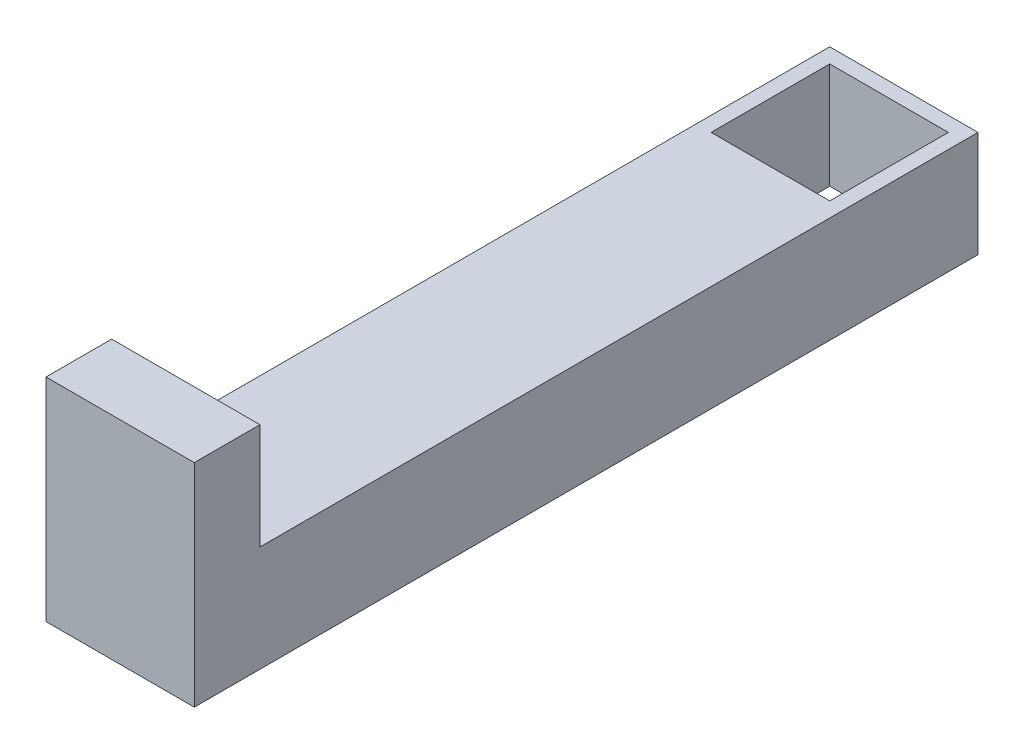
SolidWorks part; units mm, degrees
ref_plane "Front Plane" through (0, 0, 0) normal (0, 0, 1) x (1, 0, 0)
ref_plane "Top Plane" through (0, 0, 0) normal (0, 1, 0) x (1, 0, 0)
ref_plane "Right Plane" through (0, 0, 0) normal (1, 0, 0) x (0, 0, -1)
sketch "Sketch1" plane through (0, 0, 0) normal (0, 1, 0) x (1, 0, 0)
  line L1 (-1.4, -1.4) -> (1.4, -1.4)
  line L2 (-1.4, -1.4) -> (-1.4, 1.4)
  line L3 (-1.4, 1.4) -> (1.4, 1.4)
  line L4 (1.4, -1.4) -> (1.4, 1.4)
  line L5 (-1.4, -1.4) -> (1.4, 1.4) construction
  line L6 (-1.4, 1.4) -> (1.4, -1.4) construction
  line L11 (-1.75, -1.75) -> (1.75, 1.75) construction
  line L12 (-1.75, 1.75) -> (1.75, -1.75) construction
  line L13 (-1.75, 1.75) -> (1.75, 1.75)
  line L14 (-1.75, 1.75) -> (-1.75, -16.75)
  line L15 (-1.75, -16.75) -> (1.75, -16.75)
  line L16 (1.75, 1.75) -> (1.75, -16.75)
  point P0 (0, 0)
  point P6 (0, 0)
extrude "Boss-Extrude1" add sketch "Sketch1" along normal blind 2.5
sketch "Sketch4" plane through (0, 2.5, 0) normal (0, 1, 0) x (1, 0, 0)
  line L0 (1.75, -16.75) -> (1.75, 1.75) construction
  line L1 (-1.75, -16.75) -> (1.75, -16.75)
  line L2 (-1.75, -16.75) -> (-1.75, -15.2003)
  line L3 (-1.75, -15.2003) -> (1.75, -15.2003)
  line L4 (1.75, -16.75) -> (1.75, -15.2003)
extrude "Boss-Extrude2" add sketch "Sketch4" along normal blind 2.5
